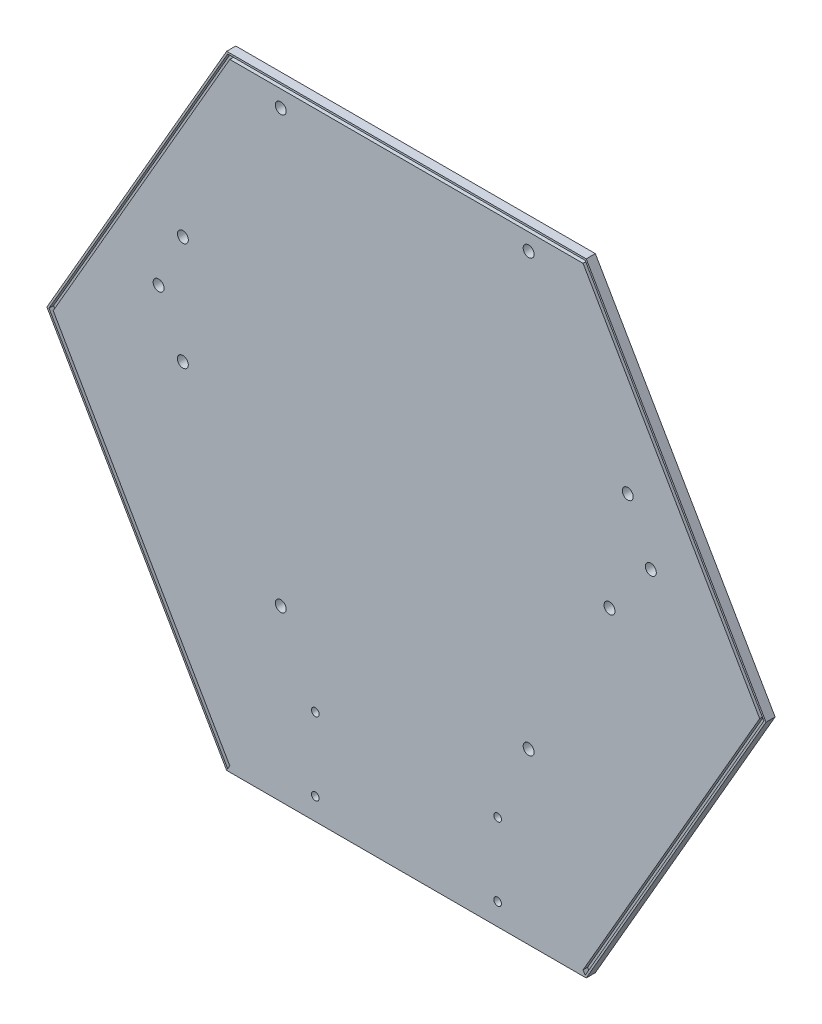
SolidWorks part; units mm, degrees
ref_plane "前视基准面" through (0, 0, 0) normal (0, 0, 1) x (1, 0, 0)
ref_plane "上视基准面" through (0, 0, 0) normal (0, 1, 0) x (1, 0, 0)
ref_plane "右视基准面" through (0, 0, 0) normal (1, 0, 0) x (0, 0, -1)
other "Configuration Table"
ref_plane "基准面1" through (0, 0, 20) normal (0, 0, 1) x (1, 0, 0)
sketch "草图51" plane through (0, 0, 20) normal (0, 0, 1) x (1, 0, 0)
  line L1 (198.1766, -40.9837) -> (99.5655, 129.8157)
  line L2 (99.5655, 129.8157) -> (-97.6567, 129.8157)
  line L3 (-97.6567, 129.8157) -> (-196.2678, -40.9837)
  line L4 (-196.2678, -40.9837) -> (-97.6567, -211.7832)
  line L5 (-97.6567, -211.7832) -> (99.5655, -211.7832)
  line L6 (99.5655, -211.7832) -> (198.1766, -40.9837)
  circle A0 centre (0.9544, -40.9837) radius 170.7994 construction
extrude "凸台-拉伸9" add sketch "草图51" along normal blind 5 separate body contours L4 L5 L6 L1 L2 L3
sketch "草图52" plane through (0, 0, 25) normal (0, 0, 1) x (1, 0, 0)
  line L0 (-195.1131, -40.9837) -> (-97.0793, 128.8157)
  line L1 (-97.0793, 128.8157) -> (98.9881, 128.8157)
  line L2 (98.9881, 128.8157) -> (197.0219, -40.9837)
  line L3 (197.0219, -40.9837) -> (98.9881, -210.7832)
  line L4 (98.9881, -210.7832) -> (97.8334, -208.7832)
  line L5 (97.8334, -208.7832) -> (194.7125, -40.9837)
  line L6 (194.7125, -40.9837) -> (97.8334, 126.8157)
  line L7 (97.8334, 126.8157) -> (-95.9246, 126.8157)
  line L8 (-95.9246, 126.8157) -> (-192.8037, -40.9837)
  line L9 (-192.8037, -40.9837) -> (-95.9246, -208.7832)
  line L10 (-95.9246, -208.7832) -> (-97.0793, -210.7832)
  line L11 (-97.0793, -210.7832) -> (-195.1131, -40.9837)
  line L12 (-196.2678, -40.9837) -> (-97.6567, -211.7832) construction
  line L13 (-97.6567, 129.8157) -> (-196.2678, -40.9837) construction
  line L14 (99.5655, 129.8157) -> (-97.6567, 129.8157) construction
  line L15 (198.1766, -40.9837) -> (99.5655, 129.8157) construction
  line L16 (99.5655, -211.7832) -> (198.1766, -40.9837) construction
  line L17 (-97.0793, -210.7832) -> (98.9881, -210.7832) construction
  line L18 (-196.2678, -40.9837) -> (-195.1131, -40.9837) construction
  line L19 (-97.6567, -211.7832) -> (99.5655, -211.7832) construction
  line L20 (-195.1131, -40.9837) -> (-192.8037, -40.9837) construction
  line L21 (-97.6567, 129.8157) -> (-97.0793, 128.8157) construction
  line L22 (-95.9246, 126.8157) -> (-97.0793, 128.8157) construction
  dimension "D1" = 1
  dimension "D2" = 1
  dimension "D3" = 2
  dimension "D4" = 2
  dimension "D5" = 2
  dimension "D6" = 1
  dimension "D7" = 1
  dimension "D8" = 2
  dimension "D9" = 1
  dimension "D10" = 2
  dimension "D11" = 1
  dimension "D12" = 60
  dimension "D13" = 60
extrude "切除-拉伸7" cut sketch "草图52" against normal blind 2.5 contours L11 L0 L1 L2 L3 L4 L5 L6 L7 L8 L9 L10
sketch "草图53" plane through (0, 0, 20) normal (0, 0, -1) x (-1, 0, 0)
  circle A0 centre (-67.98, -118.86) radius 3
  circle A1 centre (-67.98, -118.86) radius 3
  circle A2 centre (-67.98, 117.66) radius 3
  circle A3 centre (67.98, 117.66) radius 3
  circle A4 centre (-112.33, -29.68) radius 3
  circle A5 centre (121.69, -29.68) radius 3
  circle A6 centre (-135, 0) radius 3
  circle A7 centre (135, 0) radius 3
  circle A8 centre (-122.33, 29.64) radius 3
  circle A9 centre (121.69, 29.64) radius 3
  circle A10 centre (67.98, -118.86) radius 3
extrude "切除-拉伸12" cut sketch "草图53" against normal blind 5 contours A2 | A8 | A6 | A4 | A0 | A10 | A5 | A7 | A9 | A3
sketch "草图54" plane through (0, 0, 20) normal (0, 0, 1) x (1, 0, 0)
  line L0 (0.9544, 126.8157) -> (0.9544, -211.7832) construction
  line L1 (97.8334, 126.8157) -> (-95.9246, 126.8157) construction
  line L2 (-97.6567, -211.7832) -> (99.5655, -211.7832) construction
  circle A0 centre (-49.0456, -199.7832) radius 2.1
  circle A1 centre (50.9544, -199.7832) radius 2.1
  circle A2 centre (-49.0456, -159.7832) radius 2.1
  circle A3 centre (50.9544, -159.7832) radius 2.1
  point P11 (0, 0)
  point P15 (-45.5335, -181.7769)
  dimension "D3" = 50
  dimension "D1" = 12
  dimension "D2" = 50
  dimension "D4" = 40
extrude "切除-拉伸14" cut sketch "草图54" along normal through all
